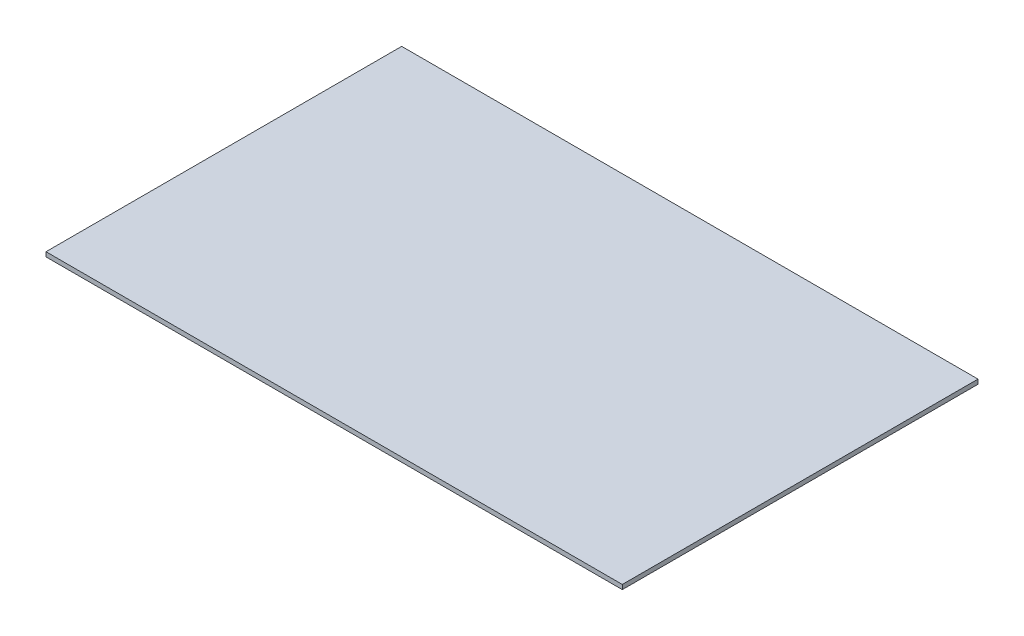
SolidWorks part; units mm, degrees
ref_plane "Plan de face" through (0, 0, 0) normal (0, 0, 1) x (1, 0, 0)
ref_plane "Plan de dessus" through (0, 0, 0) normal (0, 1, 0) x (1, 0, 0)
ref_plane "Plan de droite" through (0, 0, 0) normal (1, 0, 0) x (0, 0, -1)
sketch "Esquisse1" plane through (0, 0, 0) normal (0, 1, 0) x (1, 0, 0)
  line L1 (0, 39.5) -> (64, 39.5)
  line L2 (0, 39.5) -> (0, -39.5)
  line L3 (0, -39.5) -> (64, -39.5)
  line L4 (64, 39.5) -> (64, -39.5)
  dimension "D1" = 64
  dimension "D2" = 79
  dimension "D3" = 39.5
extrude "Boss.-Extru.1" add sketch "Esquisse1" along normal blind 1
mirror "Symétrie1" about plane through (0, 1, -39.5) normal (1, 0, 0) of "Boss.-Extru.1"
